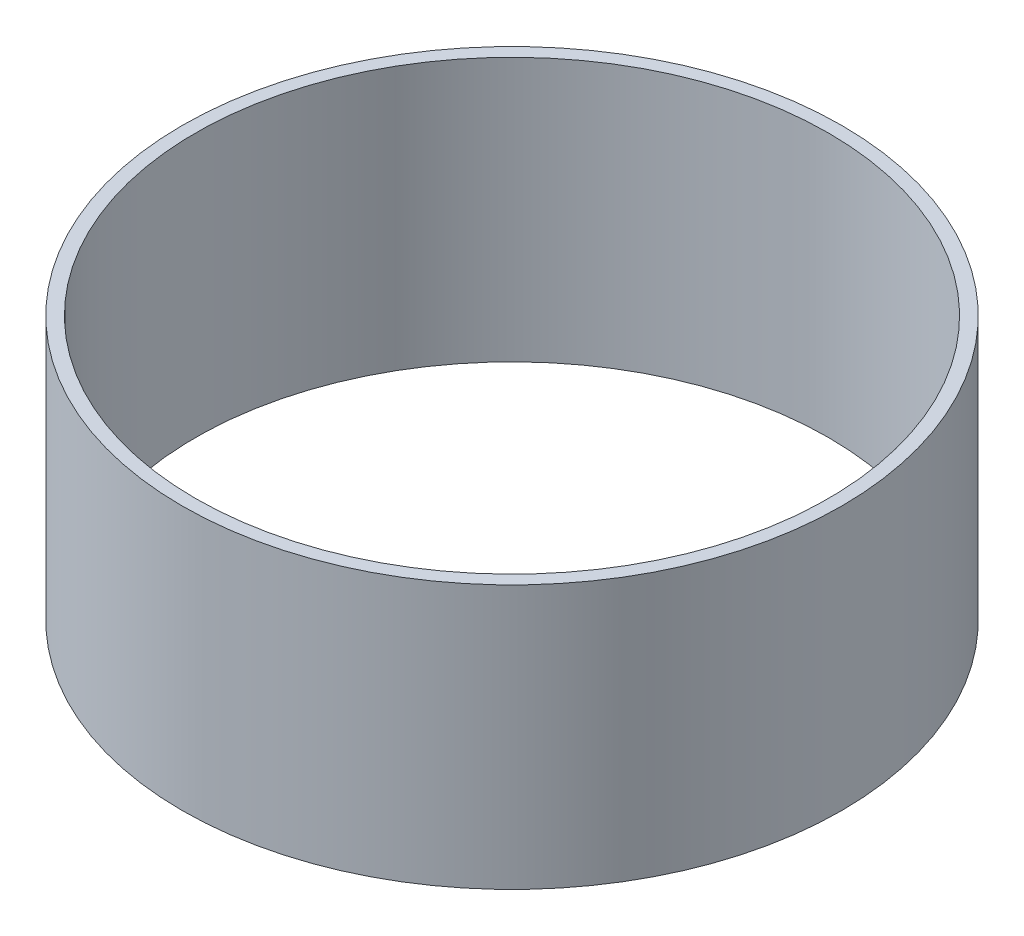
SolidWorks part; units mm, degrees
ref_plane "前视基准面" through (0, 0, 0) normal (0, 0, 1) x (1, 0, 0)
ref_plane "上视基准面" through (0, 0, 0) normal (0, 1, 0) x (1, 0, 0)
ref_plane "右视基准面" through (0, 0, 0) normal (1, 0, 0) x (0, 0, -1)
other "Configuration Table"
sketch "草图1" plane through (0, 0, 0) normal (0, 1, 0) x (1, 0, 0)
  circle A0 centre (0, 0) radius 12.5
  circle A1 centre (0, 0) radius 12
extrude "凸台-拉伸1" add sketch "草图1" along normal blind 10
